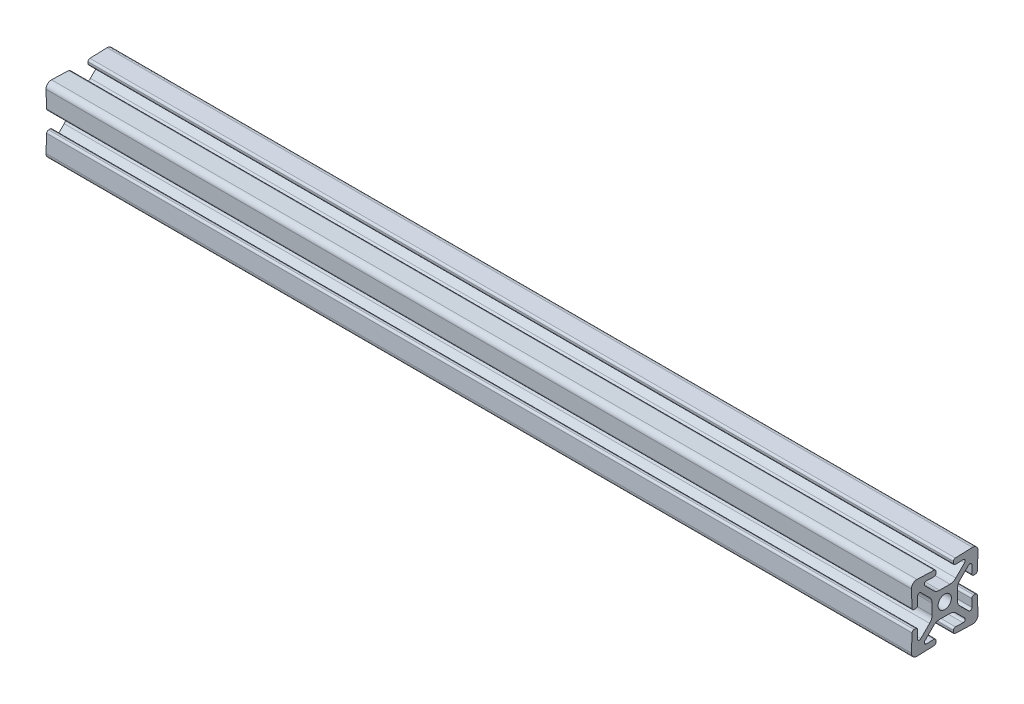
SolidWorks part; units mm, degrees
ref_plane "Front Plane" through (0, 0, 0) normal (0, 0, 1) x (1, 0, 0)
ref_plane "Top Plane" through (0, 0, 0) normal (0, 1, 0) x (1, 0, 0)
ref_plane "Right Plane" through (0, 0, 0) normal (1, 0, 0) x (0, 0, -1)
sketch "Sketch1" plane through (0, 0, 0) normal (1, 0, 0) x (0, 0, -1)
  line L0 (0, -12.7) -> (0, 12.7) construction
  line L1 (-7.874, 12.7) -> (7.874, 12.7) construction
  line L2 (-12.7, 0) -> (12.7, 0) construction
  line L3 (-7.874, 12.7) -> (-7.874, 4.826) construction
  line L4 (-3.302, 12.7) -> (3.302, 12.7) construction
  line L5 (-12.7, -12.7) -> (12.7, -12.7) construction
  line L6 (-12.7, 12.7) -> (12.7, 12.7) construction
  circle A0 centre (0, 0) radius 2.54 construction
  point P7 (0, 12.7)
  point P10 (0, 0)
  point P13 (0, 0)
  point P16 (0, 12.7)
  point P17 (-3.302, 12.7)
  point P18 (3.302, 12.7)
  point P21 (0, -12.7)
  point P24 (0, 12.7)
  dimension "Center Hole Diameter" = 5.08
  dimension "Rail Width" = 25.4
  dimension "Rail Height" = 25.4
  dimension "T-Slot Depth" = 7.874
  dimension "D1" = 15.748
  dimension "T-Slot Width" = 6.604
  dimension "D2" = 12.7
sketch "Sketch2" plane through (0, 0, 0) normal (0, 0, 1) x (1, 0, 0)
  line L0 (-165.1, 0) -> (165.1, 0) construction
  line L1 (0, 0) -> (0, 26.104) construction
  line L2 (165.1, -12.7) -> (165.1, 12.7) construction
  line L3 (-165.1, -12.7) -> (-165.1, 12.7) construction
  point P3 (-127, 0)
  point P8 (0, 0)
  point P9 (127, 0)
  point P12 (165.1, 0)
  point P15 (-165.1, 0)
  dimension "Length" = 330.2
  dimension "D1" = 38.1
  dimension "D2" = 25.4
sketch "Sketch3" plane through (0, 0, 0) normal (1, 0, 0) x (0, 0, -1)
  line L0 (0, 4.826) -> (1.9842, 4.826)
  line L1 (0, -12.7) -> (0, 12.7) construction
  line L2 (4.2293, 5.7559) -> (7.5866, 9.1132)
  line L6 (7.0212, 10.4136) -> (4.0906, 10.3112)
  line L7 (3.302, 11.0728) -> (3.302, 11.7082)
  line L8 (-7.874, 12.7) -> (7.874, 12.7) construction
  line L10 (0, 0) -> (12.7, 12.7) construction
  line L13 (0, 4.826) -> (0, 2.54)
  line L14 (4.826, 0) -> (2.54, 0)
  line L31 (4.826, 0) -> (4.826, 1.9842)
  line L32 (4.0374, 12.4697) -> (10.5971, 12.6988)
  line L33 (-12.7, 0) -> (12.7, 0) construction
  line L34 (-12.7, 12.7) -> (12.7, 12.7) construction
  line L35 (5.7559, 4.2293) -> (9.1132, 7.5866)
  line L36 (0, 12.7) -> (12.7, 12.7) construction
  line L37 (12.7, 12.7) -> (12.7, 8.0234) construction
  line L38 (11.0728, 3.302) -> (11.7082, 3.302)
  line L39 (10.4136, 7.0212) -> (10.3112, 4.0906)
  line L40 (12.6988, 10.5971) -> (12.4697, 4.0374)
  arc A0 (2.54, 0) -> (0, 2.54) centre (0, 0) ccw
  arc A1 (1.9842, 4.826) -> (4.2293, 5.7559) centre (1.9842, 8.001) ccw
  circle A2 centre (0, 0) radius 2.54 construction
  arc A7 (3.302, 11.7082) -> (4.0374, 12.4697) centre (4.064, 11.7082) cw
  arc A8 (4.0906, 10.3112) -> (3.302, 11.0728) centre (4.064, 11.0728) cw
  arc A14 (4.826, 1.9842) -> (5.7559, 4.2293) centre (8.001, 1.9842) cw
  arc A16 (10.5971, 12.6988) -> (12.6988, 10.5971) centre (10.668, 10.668) cw
  arc A17 (7.0212, 10.4136) -> (7.5866, 9.1132) centre (7.0478, 9.652) cw
  arc A18 (10.4136, 7.0212) -> (9.1132, 7.5866) centre (9.652, 7.0478) ccw
  arc A19 (10.3112, 4.0906) -> (11.0728, 3.302) centre (11.0728, 4.064) ccw
  arc A20 (11.7082, 3.302) -> (12.4697, 4.0374) centre (11.7082, 4.064) ccw
  point P37 (3.2994, 4.826)
  point P49 (12.7, 3.302)
  point P52 (3.302, 12.7)
  point P55 (3.302, 10.2837)
  dimension "D4" = 3.175
  dimension "D9" = 2.159
  dimension "D12" = 0.762
  dimension "D3" = 2.032
  dimension "D8" = 0.762
  dimension "D2" = 45
  dimension "D5" = 2
  dimension "D6" = 45
  dimension "D7" = 2.159
extrude "Boss-Extrude1" add sketch "Sketch3" against normal up to vertex (165.1 mm away) and the other way up to vertex (165.1 mm away) up to point (-165.1, 0, 0) other way up to point (165.1, 0, 0)
mirror "Mirror1" about plane through (0, 0, 0) normal (0, 1, 0) of bodies 104
mirror "Mirror2" about plane through (0, 0, 0) normal (0, 0, 1) of bodies 105
equation "\"D1@Sketch2\"=\"Rail Height@Sketch1\"*1.5"
equation "\"D2@Sketch2\"=\"Rail Height@Sketch1\""
